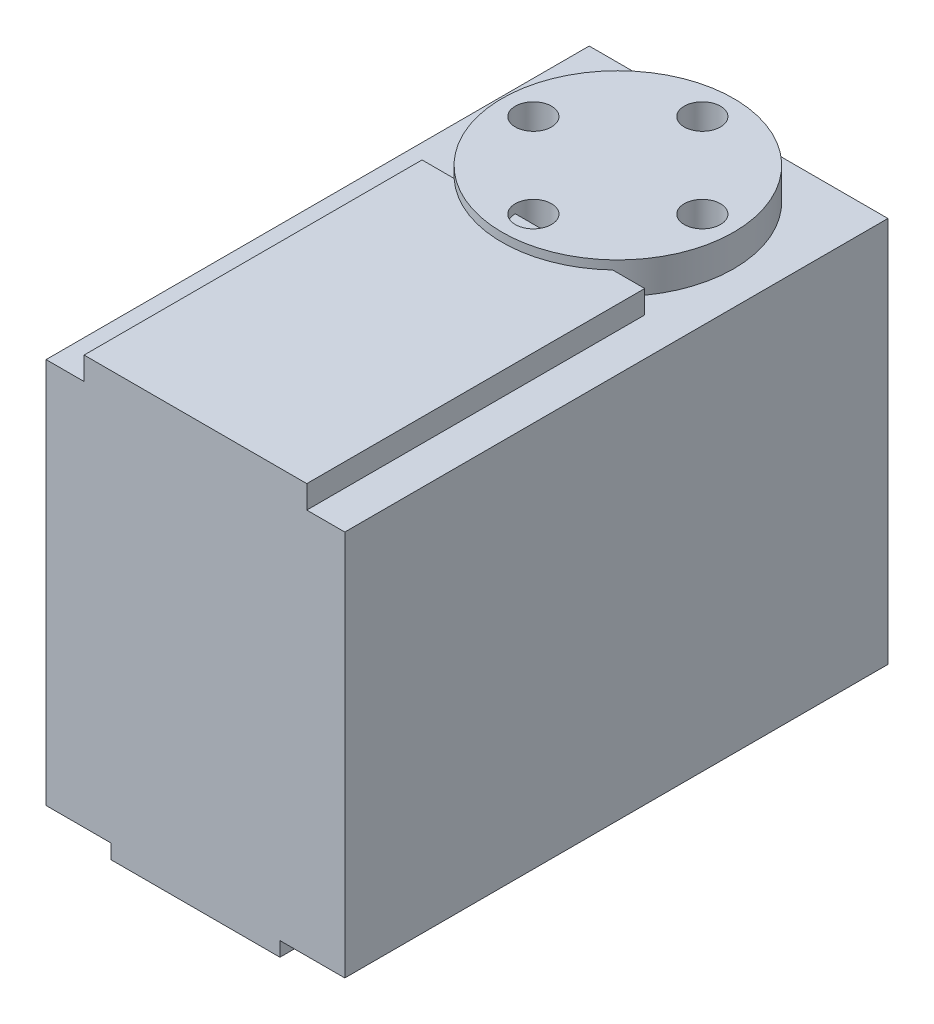
SolidWorks part; units mm, degrees
ref_plane "前视基准面" through (0, 0, 0) normal (0, 0, 1) x (1, 0, 0)
ref_plane "上视基准面" through (0, 0, 0) normal (0, 1, 0) x (1, 0, 0)
ref_plane "右视基准面" through (0, 0, 0) normal (1, 0, 0) x (0, 0, -1)
other "Configuration Table"
sketch "草图1" plane through (0, 0, 0) normal (0, 0, 1) x (1, 0, 0)
  line L1 (-12.7455, 9.7567) -> (12.0045, 9.7567)
  line L2 (-12.7455, 9.7567) -> (-12.7455, -22.2433)
  line L3 (-12.7455, -22.2433) -> (12.0045, -22.2433)
  line L4 (12.0045, 9.7567) -> (12.0045, -22.2433)
  dimension "D1" = 24.75
  dimension "D2" = 32
extrude "凸台-拉伸1" add sketch "草图1" along normal blind 45
sketch "草图2" plane through (0, 0, 45) normal (0, 0, 1) x (1, 0, 0)
  line L0 (-9.5955, 9.7567) -> (-9.5955, 11.6567)
  line L1 (12.0045, 9.7567) -> (-12.7455, 9.7567) construction
  line L2 (-9.5955, 11.6567) -> (8.8545, 11.6567)
  line L3 (8.8545, 11.6567) -> (8.8545, 9.7567)
  line L4 (8.8545, 9.7567) -> (-9.5955, 9.7567)
  line L5 (-12.7455, 9.7567) -> (-12.7455, -22.2433) construction
  line L6 (12.0045, -22.2433) -> (12.0045, 9.7567) construction
  line L7 (6.6295, -22.2433) -> (-7.3705, -22.2433)
  line L8 (6.6295, -23.4433) -> (6.6295, -22.2433)
  line L9 (-7.3705, -23.4433) -> (6.6295, -23.4433)
  line L10 (-7.3705, -22.2433) -> (-7.3705, -23.4433)
  point P8 (-0.3705, -23.4433)
  dimension "D1" = 3.15
  dimension "D2" = 18.45
  dimension "D3" = 1.2
  dimension "D4" = 1.9
  dimension "D5" = 14
  dimension "D6" = 12.375
extrude "凸台-拉伸2" add sketch "草图2" against normal blind 28
sketch "草图3" plane through (0, 9.7567, 0) normal (0, 1, 0) x (1, 0, 0)
  line L0 (-0.3705, -45) -> (-0.3705, 10.6772) construction
  line L1 (8.8545, -45) -> (-9.5955, -45) construction
  circle A0 centre (-0.3705, -10) radius 9.6
  dimension "D2" = 19.2
  dimension "D1" = 35
ref_plane "基准面1" through (0, -6.2433, 0) normal (0, 1, 0) x (1, 0, 0)
sketch "草图4" plane through (0, -6.2433, 0) normal (0, 1, 0) x (1, 0, 0)
  line L0 (-0.3705, -45) -> (-0.3705, 10.6772) construction
  circle A0 centre (-0.3705, -10) radius 9.6
  circle A1 centre (-0.3705, -3) radius 1.5
  circle A2 centre (6.6295, -10) radius 1.5
  circle A3 centre (-0.3705, -17) radius 1.5
  circle A4 centre (-7.3705, -10) radius 1.5
  point P16 (-0.3705, -10)
  dimension "D2" = 3
  dimension "D1" = 7
  dimension "D3" = 4
extrude "凸台-拉伸3" add sketch "草图4" along normal mid plane 37.25
sketch "草图6" plane through (0, 0, 45) normal (0, 0, 1) x (1, 0, 0)
  line L0 (-9.5955, 11.6567) -> (-9.5955, 9.7567)
sketch "草图7" plane through (0, 11.6567, 0) normal (0, 1, 0) x (1, 0, 0)
  line L0 (-0.3705, -19.6) -> (-0.3705, -45)
  line L1 (8.8545, -45) -> (-9.5955, -45) construction
  arc A0 (-6.9401, -17) -> (6.1991, -17) centre (-0.3705, -10) ccw construction
sketch "草图10" plane through (0, 0, 45) normal (0, 0, 1) x (1, 0, 0)
  line L0 (6.6295, -23.4433) -> (6.6295, -22.2433)
sketch "草图12" plane through (0, 0, 45) normal (0, 0, 1) x (1, 0, 0)
  line L0 (-12.7455, 9.7567) -> (-12.7455, -22.2433)
sketch "草图13" plane through (12.0045, 0, 0) normal (1, 0, 0) x (0, 0, -1)
  line L0 (-45, 11.6567) -> (-45, 9.7567) construction
  line L1 (-45, 9.7567) -> (0, 9.7567)
  line L2 (-45, 9.7567) -> (-45, -22.2433)
  line L3 (-45, -22.2433) -> (0, -22.2433)
  line L4 (0, 9.7567) -> (0, -22.2433)
  line L5 (-45, 9.7567) -> (-45, -22.2433) construction
  dimension "D1" = 45
  dimension "D2" = 32
